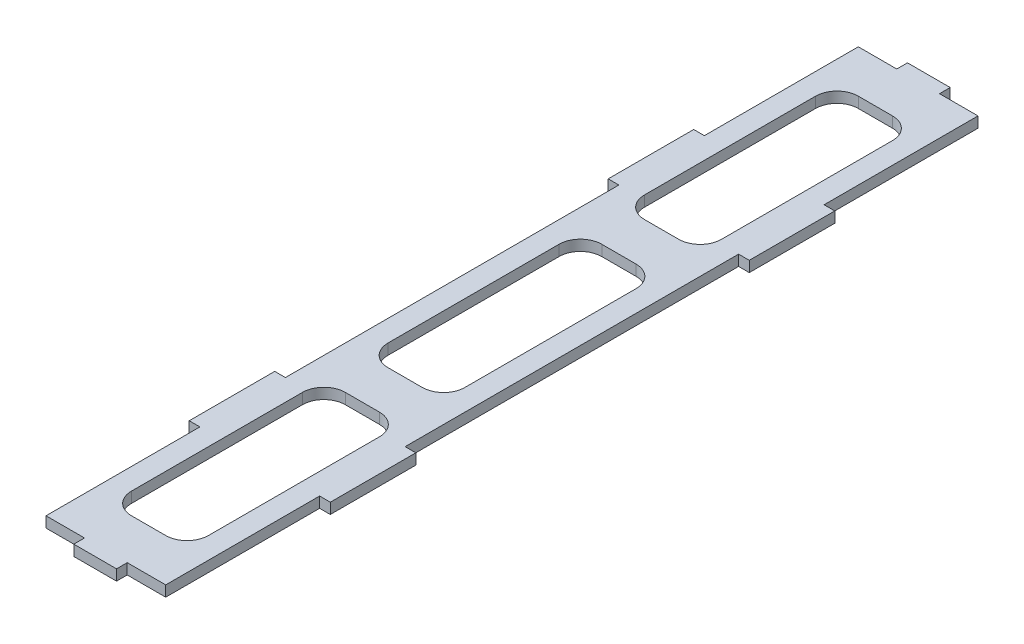
SolidWorks part; units mm, degrees
ref_plane "Front Plane" through (0, 0, 0) normal (0, 0, 1) x (1, 0, 0)
ref_plane "Top Plane" through (0, 0, 0) normal (0, 1, 0) x (1, 0, 0)
ref_plane "Right Plane" through (0, 0, 0) normal (1, 0, 0) x (0, 0, -1)
sketch "Sketch2" plane through (0, 0, 0) normal (0, 1, 0) x (1, 0, 0)
  line L1 (35.56, 0) -> (35.56, 45.72)
  line L2 (35.56, 45.72) -> (38.735, 45.72)
  line L3 (38.735, 45.72) -> (38.735, 71.12)
  line L4 (38.735, 71.12) -> (35.56, 71.12)
  line L5 (35.56, 71.12) -> (35.56, 170.18)
  line L6 (35.56, 170.18) -> (38.735, 170.18)
  line L7 (38.735, 170.18) -> (38.735, 195.58)
  line L8 (38.735, 195.58) -> (35.56, 195.58)
  line L9 (35.56, 195.58) -> (35.56, 241.3)
  line L11 (0, 241.3) -> (0, 195.58)
  line L12 (0, 195.58) -> (-3.175, 195.58)
  line L13 (-3.175, 195.58) -> (-3.175, 170.18)
  line L14 (-3.175, 170.18) -> (0, 170.18)
  line L15 (0, 170.18) -> (0, 71.12)
  line L16 (0, 71.12) -> (-3.175, 71.12)
  line L17 (-3.175, 71.12) -> (-3.175, 45.72)
  line L18 (-3.175, 45.72) -> (0, 45.72)
  line L19 (0, 45.72) -> (0, 0)
  line L20 (0, 0) -> (11.43, 0)
  line L21 (11.43, 0) -> (11.43, -3.175)
  line L22 (11.43, -3.175) -> (24.13, -3.175)
  line L23 (24.13, -3.175) -> (24.13, 0)
  line L25 (0, 241.3) -> (11.43, 241.3)
  line L26 (11.43, 241.3) -> (11.43, 244.475)
  line L27 (11.43, 244.475) -> (24.13, 244.475)
  line L28 (24.13, 244.475) -> (24.13, 241.3)
  line L29 (24.13, 241.3) -> (35.56, 241.3)
  line L30 (24.13, 0) -> (35.56, 0)
extrude "Boss-Extrude1" add sketch "Sketch2" along normal blind 3.175
sketch "Sketch3" plane through (0, 0, 0) normal (0, 1, 0) x (1, 0, 0)
  line L2 (6.35, 12.7) -> (29.21, 12.7)
  line L3 (29.21, 12.7) -> (29.21, 76.2)
  line L4 (6.35, 12.7) -> (6.35, 76.2)
  line L6 (29.21, 88.9) -> (6.35, 88.9)
  line L8 (29.21, 88.9) -> (29.21, 152.4)
  line L9 (6.35, 88.9) -> (6.35, 152.4)
  line L10 (6.35, 152.4) -> (29.21, 152.4)
  line L13 (29.21, 165.1) -> (29.21, 228.6)
  line L14 (6.35, 165.1) -> (6.35, 228.6)
  line L15 (6.35, 228.6) -> (29.21, 228.6)
  line L18 (6.35, 76.2) -> (29.21, 76.2)
  line L19 (29.21, 165.1) -> (6.35, 165.1)
extrude "Cut-Extrude2" cut sketch "Sketch3" along normal blind 3.175
fillet "Fillet3" radius 6.35 12 edges at (6.35, 1.5875, -228.6) (6.35, 1.5875, -152.4) (6.35, 1.5875, -76.2) (29.21, 1.5875, -228.6) (29.21, 1.5875, -152.4) (29.21, 1.5875, -76.2) (6.35, 1.5875, -165.1) (6.35, 1.5875, -88.9) (29.21, 1.5875, -165.1) (29.21, 1.5875, -88.9) (29.21, 1.5875, -12.7) (6.35, 1.5875, -12.7)
